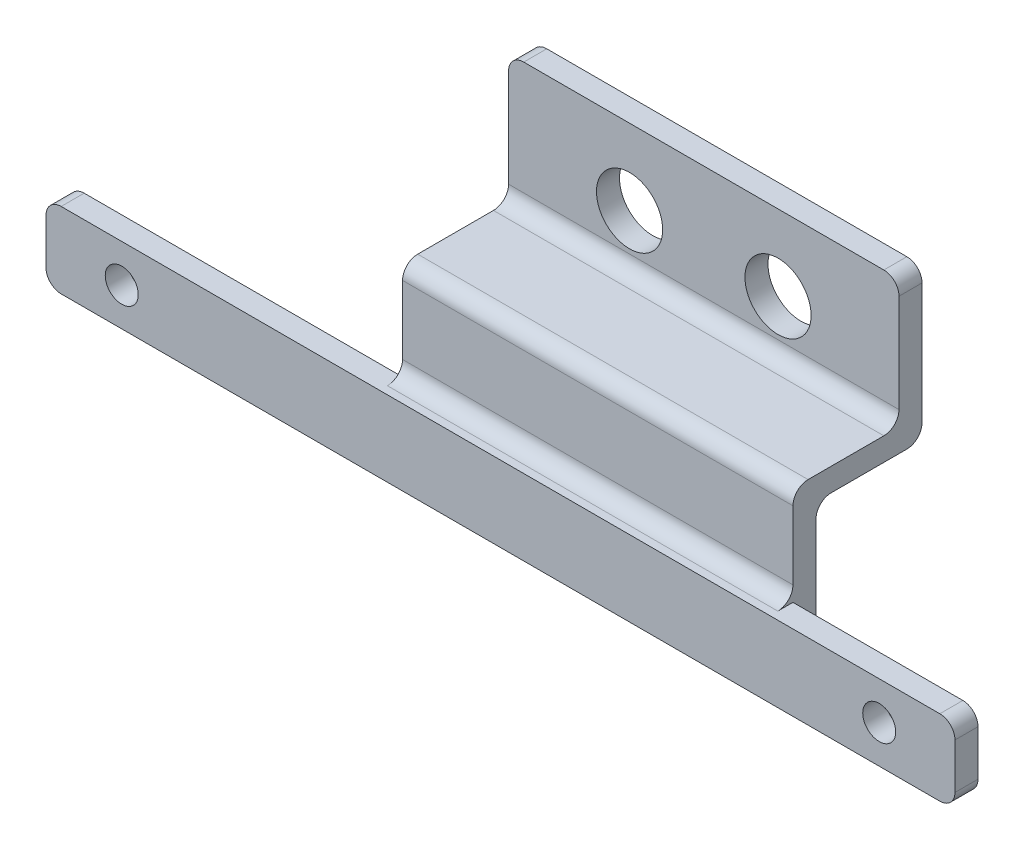
SolidWorks part; units mm, degrees
material "1060 Alloy"
ref_plane "Front" through (0, 0, 0) normal (0, 0, 1) x (1, 0, 0)
ref_plane "Top" through (0, 0, 0) normal (0, 1, 0) x (1, 0, 0)
ref_plane "Right" through (0, 0, 0) normal (1, 0, 0) x (0, 0, -1)
sketch "Sketch1" plane through (0, 0, 0) normal (0, 0, 1) x (1, 0, 0)
  line L0 (-12.885, 5) -> (12.885, 5)
  line L1 (12.885, 5) -> (12.885, -5)
  line L2 (-12.885, 5) -> (-12.885, -5)
  line L3 (-12.885, -5) -> (12.885, -5)
  line L4 (0, 5) -> (0, -5) construction
  line L5 (-4.9, 0) -> (4.9, 0) construction
  line L6 (-12.885, 0) -> (12.885, 0) construction
  circle A0 centre (-4.9, 0) radius 2.185
  circle A1 centre (4.9, 0) radius 2.185
  point P12 (0, 0)
  dimension "D1" = 4.37
  dimension "D2" = 9.8
  dimension "D3" = 4.9
  dimension "D4" = 10
  dimension "D5" = 25.77
extrude "Boss-Extrude1" add sketch "Sketch1" along normal blind 1.52
ref_plane "Plane1" through (0, 0, 1.52) normal (0, 0, 1) x (1, 0, 0)
sketch "Sketch2" plane through (0, 0, 1.52) normal (0, 0, 1) x (1, 0, 0)
  line L0 (-12.885, -5) -> (-12.885, -3.48)
  line L1 (-12.885, 5) -> (-12.885, -5) construction
  line L2 (-12.885, -3.48) -> (12.885, -3.48)
  line L3 (12.885, -5) -> (12.885, 5) construction
  line L4 (12.885, -3.48) -> (12.885, -5)
  line L5 (-12.885, -5) -> (12.885, -5)
  dimension "D1" = 1.52
extrude "Boss-Extrude2" add sketch "Sketch2" along normal blind 7
ref_plane "Plane2" through (0, -5, 0) normal (0, -1, 0) x (-1, 0, 0)
sketch "Sketch3" plane through (0, -5, 0) normal (0, -1, 0) x (-1, 0, 0)
  line L0 (-12.885, -8.52) -> (12.885, -8.52)
  line L1 (12.885, -8.52) -> (12.885, -7)
  line L2 (12.885, -8.52) -> (12.885, 0) construction
  line L3 (12.885, -7) -> (-12.885, -7)
  line L4 (-12.885, -8.52) -> (-12.885, 0) construction
  line L5 (-12.885, -7) -> (-12.885, -8.52)
  dimension "D1" = 1.52
extrude "Boss-Extrude3" add sketch "Sketch3" along normal blind 10
ref_plane "Plane3" through (0, 0, 8.52) normal (0, 0, 1) x (1, 0, 0)
sketch "Sketch4" plane through (0, 0, 8.52) normal (0, 0, 1) x (1, 0, 0)
  line L0 (-12.885, -15) -> (-34.9, -15)
  line L1 (-34.9, -15) -> (-34.9, -10)
  line L2 (-34.9, -10) -> (25.1, -10)
  line L3 (25.1, -10) -> (25.1, -15)
  line L4 (25.1, -15) -> (-12.885, -15)
  line L5 (0, 5) -> (0, -15) construction
  line L6 (12.885, 5) -> (-12.885, 5) construction
  dimension "D1" = 60
  dimension "D2" = 34.9
  dimension "D3" = 5
extrude "Boss-Extrude4" add sketch "Sketch4" along normal blind 1.52
sketch "Sketch5" plane through (0, 0, 8.52) normal (0, 0, 1) x (1, 0, 0)
  line L0 (-34.9, -12.5) -> (25.1, -12.5) construction
  line L1 (-34.9, -10) -> (-34.9, -15) construction
  line L2 (25.1, -15) -> (25.1, -10) construction
  line L4 (-34.9, -15) -> (25.1, -15) construction
  line L5 (-4.9, -10) -> (-4.9, -15) construction
  line L6 (25.1, -10) -> (-34.9, -10) construction
  circle A0 centre (-29.9, -12.5) radius 1.09
  circle A1 centre (20.1, -12.5) radius 1.09
  dimension "D1" = 2.18
  dimension "D2" = 25
extrude "Cut-Extrude1" cut sketch "Sketch5" against normal mid plane 10
fillet "Fillet1" radius 1 12 edges at (0, -3.48, 8.52) (0, -10, 8.52) (25.1, -15, 9.28) (25.1, -10, 9.28) (-34.9, -15, 9.28) (-34.9, -10, 9.28) (0, -5, 0) (-12.885, 5, 0.76) (12.885, 5, 0.76) (0, -15, 7)
